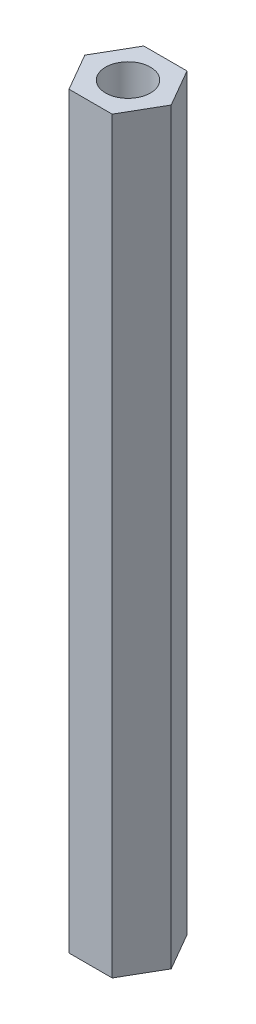
SolidWorks part; units mm, degrees
ref_plane "Front Plane" through (0, 0, 0) normal (0, 0, 1) x (1, 0, 0)
ref_plane "Top Plane" through (0, 0, 0) normal (0, 1, 0) x (1, 0, 0)
ref_plane "Right Plane" through (0, 0, 0) normal (1, 0, 0) x (0, 0, -1)
sketch "Sketch1" plane through (0, 0, 0) normal (0, 1, 0) x (1, 0, 0)
  line L1 (4.0415, 0) -> (2.0207, 3.5)
  line L2 (2.0207, 3.5) -> (-2.0207, 3.5)
  line L3 (-2.0207, 3.5) -> (-4.0415, 0)
  line L4 (-4.0415, 0) -> (-2.0207, -3.5)
  line L5 (-2.0207, -3.5) -> (2.0207, -3.5)
  line L6 (2.0207, -3.5) -> (4.0415, 0)
  circle A0 centre (0, 0) radius 2.1
  circle A2 centre (0, 0) radius 3.5 construction
  dimension "D1" = 4.2
  dimension "D2" = 7
extrude "Boss-Extrude1" add sketch "Sketch1" along normal blind 70
